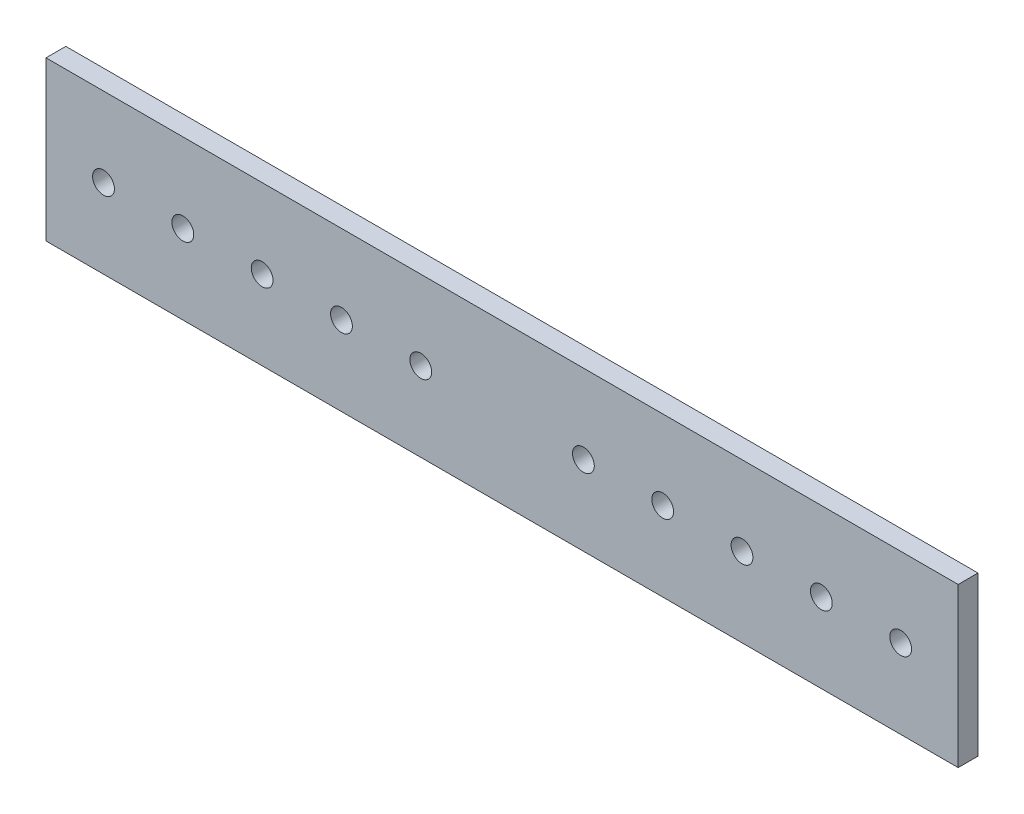
SolidWorks part; units mm, degrees
ref_plane "Plan de face" through (0, 0, 0) normal (0, 0, 1) x (1, 0, 0)
ref_plane "Plan de dessus" through (0, 0, 0) normal (0, 1, 0) x (1, 0, 0)
ref_plane "Plan de droite" through (0, 0, 0) normal (1, 0, 0) x (0, 0, -1)
sketch "Esquisse1" plane through (0, 0, 0) normal (0, 0, 1) x (1, 0, 0)
  line L1 (-115, -20) -> (115, -20)
  line L2 (-115, -20) -> (-115, 20)
  line L3 (-115, 20) -> (115, 20)
  line L4 (115, -20) -> (115, 20)
  line L5 (-115, -20) -> (115, 20) construction
  line L6 (-115, 20) -> (115, -20) construction
  point P0 (0, 0)
  dimension "D1" = 230
  dimension "D2" = 40
extrude "Boss.-Extru.1" add sketch "Esquisse1" along normal blind 5
sketch "Esquisse2" plane through (0, 0, 5) normal (0, 0, 1) x (1, 0, 0)
  circle A0 centre (0, 0) radius 20.5 construction
  circle A1 centre (20.5, 0) radius 2.75
  dimension "D1" = 41
  dimension "D2" = 5.5
extrude "Enlèv. mat.-Extru.1" cut sketch "Esquisse2" against normal through all
sketch "Esquisse8" plane through (0, 0, 0) normal (0, 0, -1) x (-1, 0, 0)
  circle A0 centre (20.5, 0) radius 2.75
  dimension "D2" = 5.5
  dimension "D1" = 20.5
extrude "Enlèv. mat.-Extru.2" cut sketch "Esquisse8" against normal blind 5
pattern_linear "Répétition linéaire2" count 5 spacing 20 along (1, 0, 0) of "Enlèv. mat.-Extru.1"
pattern_linear "Répétition linéaire3" count 5 spacing 20 along (-1, 0, 0) of "Enlèv. mat.-Extru.2"
